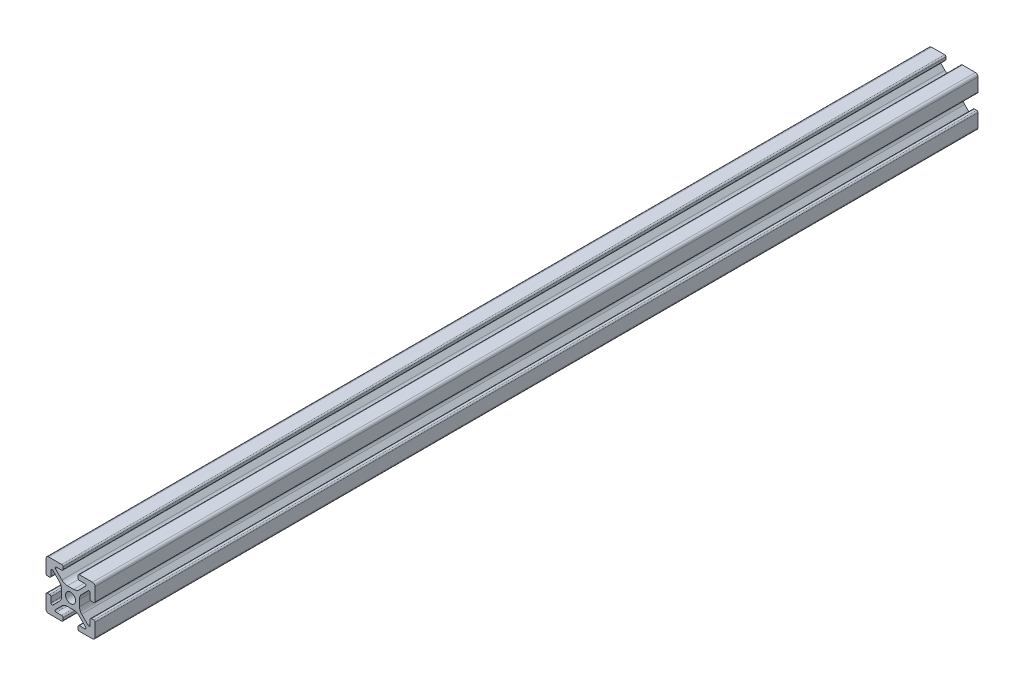
SolidWorks part; units mm, degrees
ref_plane "Front Plane" through (0, 0, 0) normal (0, 0, 1) x (1, 0, 0)
ref_plane "Top Plane" through (0, 0, 0) normal (0, 1, 0) x (1, 0, 0)
ref_plane "Right Plane" through (0, 0, 0) normal (1, 0, 0) x (0, 0, -1)
sketch "Sketch2" plane through (0, 0, 0) normal (0, 0, 1) x (1, 0, 0)
  line L0 (-3.6422, 1.2878) -> (-3.6422, -1.2878)
  line L1 (-1.2878, 3.6422) -> (1.2878, 3.6422)
  line L2 (-9.4433, 3.069) -> (-8.553, 3.069)
  line L3 (0, 0) -> (-15.7854, 0) construction
  line L4 (-3.4964, 4.5571) -> (-6.1213, 7.182)
  line L5 (-3.622, 8) -> (-5.7825, 8)
  line L6 (-3.069, 9.4433) -> (-3.069, 8.553)
  line L7 (-3.622, 10) -> (-8.939, 10)
  line L8 (0, 0) -> (0, 15.0393) construction
  line L9 (10, 3.622) -> (10, 8.939)
  line L10 (8, 3.622) -> (8, 5.7825)
  line L11 (4.5571, 3.4964) -> (7.182, 6.1213)
  line L12 (3.622, 10) -> (8.939, 10)
  line L13 (3.069, 9.4433) -> (3.069, 8.553)
  line L14 (3.622, 8) -> (5.7825, 8)
  line L15 (3.4964, 4.5571) -> (6.1213, 7.182)
  line L16 (9.4433, 3.069) -> (8.553, 3.069)
  line L17 (3.6422, 1.2878) -> (3.6422, -1.2878)
  line L18 (-10, -3.622) -> (-10, -8.939)
  line L19 (-8, -3.622) -> (-8, -5.7825)
  line L20 (-4.5571, -3.4964) -> (-7.182, -6.1213)
  line L21 (9.4433, -3.069) -> (8.553, -3.069)
  line L22 (3.4964, -4.5571) -> (6.1213, -7.182)
  line L23 (3.622, -8) -> (5.7825, -8)
  line L24 (3.069, -9.4433) -> (3.069, -8.553)
  line L25 (3.622, -10) -> (8.939, -10)
  line L26 (4.5571, -3.4964) -> (7.182, -6.1213)
  line L27 (8, -3.622) -> (8, -5.7825)
  line L28 (10, -3.622) -> (10, -8.939)
  line L29 (-3.622, -10) -> (-8.939, -10)
  line L30 (-3.069, -9.4433) -> (-3.069, -8.553)
  line L31 (-3.622, -8) -> (-5.7825, -8)
  line L32 (-3.4964, -4.5571) -> (-6.1213, -7.182)
  line L33 (-9.4433, -3.069) -> (-8.553, -3.069)
  line L34 (-1.2878, -3.6422) -> (1.2878, -3.6422)
  line L48 (-4.5571, 3.4964) -> (-7.182, 6.1213)
  line L49 (-8, 3.622) -> (-8, 5.7825)
  line L52 (-10, 3.622) -> (-10, 8.939)
  arc A0 (-8.553, 3.069) -> (-8, 3.622) centre (-8.553, 3.622) ccw
  arc A1 (-8, 5.7825) -> (-7.182, 6.1213) centre (-7.5208, 5.7825) cw
  arc A2 (-4.5571, 3.4964) -> (-3.6422, 1.2878) centre (-6.7657, 1.2878) cw
  arc A3 (-3.4964, 4.5571) -> (-1.2878, 3.6422) centre (-1.2878, 6.7657) ccw
  arc A4 (-5.7825, 8) -> (-6.1213, 7.182) centre (-5.7825, 7.5208) ccw
  arc A5 (-3.622, 10) -> (-3.069, 9.4433) centre (-3.622, 9.447) cw
  arc A6 (-3.069, 8.553) -> (-3.622, 8) centre (-3.622, 8.553) cw
  arc A7 (8.939, 10) -> (10, 8.939) centre (8.939, 8.939) cw
  arc A8 (10, 3.622) -> (9.4433, 3.069) centre (9.447, 3.622) cw
  arc A9 (3.069, 8.553) -> (3.622, 8) centre (3.622, 8.553) ccw
  arc A10 (3.622, 10) -> (3.069, 9.4433) centre (3.622, 9.447) ccw
  arc A11 (5.7825, 8) -> (6.1213, 7.182) centre (5.7825, 7.5208) cw
  arc A12 (3.4964, 4.5571) -> (1.2878, 3.6422) centre (1.2878, 6.7657) cw
  arc A13 (4.5571, 3.4964) -> (3.6422, 1.2878) centre (6.7657, 1.2878) ccw
  arc A14 (8, 5.7825) -> (7.182, 6.1213) centre (7.5208, 5.7825) ccw
  arc A15 (8.553, 3.069) -> (8, 3.622) centre (8.553, 3.622) cw
  arc A16 (-8.939, -10) -> (-10, -8.939) centre (-8.939, -8.939) cw
  arc A17 (-10, -3.622) -> (-9.4433, -3.069) centre (-9.447, -3.622) cw
  arc A18 (8.553, -3.069) -> (8, -3.622) centre (8.553, -3.622) ccw
  arc A19 (8, -5.7825) -> (7.182, -6.1213) centre (7.5208, -5.7825) cw
  arc A20 (4.5571, -3.4964) -> (3.6422, -1.2878) centre (6.7657, -1.2878) cw
  arc A21 (3.4964, -4.5571) -> (1.2878, -3.6422) centre (1.2878, -6.7657) ccw
  arc A22 (5.7825, -8) -> (6.1213, -7.182) centre (5.7825, -7.5208) ccw
  arc A23 (3.622, -10) -> (3.069, -9.4433) centre (3.622, -9.447) cw
  arc A24 (3.069, -8.553) -> (3.622, -8) centre (3.622, -8.553) cw
  arc A25 (10, -3.622) -> (9.4433, -3.069) centre (9.447, -3.622) ccw
  arc A26 (8.939, -10) -> (10, -8.939) centre (8.939, -8.939) ccw
  arc A27 (-3.069, -8.553) -> (-3.622, -8) centre (-3.622, -8.553) ccw
  arc A28 (-3.622, -10) -> (-3.069, -9.4433) centre (-3.622, -9.447) ccw
  arc A29 (-5.7825, -8) -> (-6.1213, -7.182) centre (-5.7825, -7.5208) cw
  arc A30 (-3.4964, -4.5571) -> (-1.2878, -3.6422) centre (-1.2878, -6.7657) cw
  arc A31 (-4.5571, -3.4964) -> (-3.6422, -1.2878) centre (-6.7657, -1.2878) ccw
  arc A32 (-8, -5.7825) -> (-7.182, -6.1213) centre (-7.5208, -5.7825) ccw
  arc A33 (-8.553, -3.069) -> (-8, -3.622) centre (-8.553, -3.622) cw
  arc A51 (-10, 3.622) -> (-9.4433, 3.069) centre (-9.447, 3.622) ccw
  arc A56 (-8.939, 10) -> (-10, 8.939) centre (-8.939, 8.939) ccw
  circle A57 centre (0, 0) radius 2.05
  point P1 (-3.6422, 0)
  point P46 (0, 0)
  point P48 (0, 0)
  point P53 (0, 3.6422)
  point P60 (0, 0)
  point P61 (0, 0)
  point P62 (0, 0)
  point P74 (0, 0)
  point P85 (0, 0)
  point P87 (0, 0)
  point P99 (0, 0)
  point P101 (0, 0)
  point P102 (0, 0)
  point P116 (0, -3.6422)
  point P117 (3.6422, 0)
  point P123 (0, 0)
  point P125 (0, 0)
  point P127 (0, 0)
  point P139 (0, 0)
  point P140 (0, 0)
  point P141 (0, 0)
  point P142 (0, 0)
  point P179 (0, 0)
  point P192 (0, 0)
  point P193 (0, 0)
  dimension "D1" = 0.553
  dimension "D3" = 3.1235
  dimension "D4" = 0.553
  dimension "D2" = 0.4792
  dimension "D5" = 1.061
  dimension "D6" = 2.05
extrude "Boss-Extrude1" add sketch "Sketch2" against normal blind 360
sketch "Sketch3" plane through (0, 10, 0) normal (0, 1, 0) x (1, 0, 0)
  line L0 (8.939, 0) -> (3.622, 0) construction
  line L1 (10, 360) -> (10, 0) construction
  circle A0 centre (0, 110) radius 2.75
  dimension "D2" = 5.5
  dimension "D1" = 110
  dimension "D3" = 10
extrude "Cut-Extrude1" cut sketch "Sketch3" against normal blind 34
